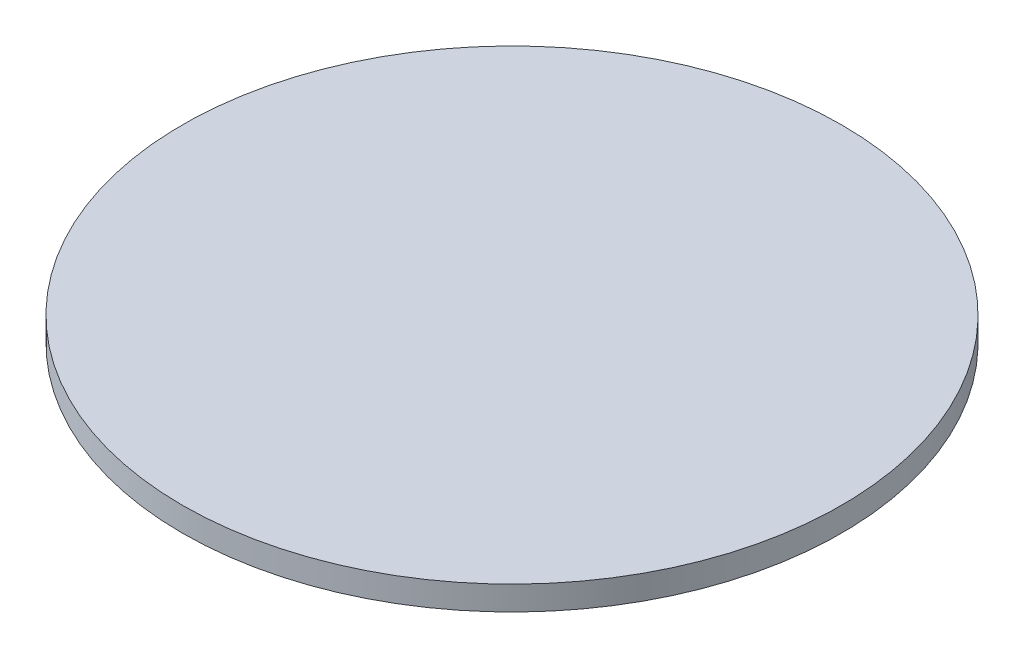
SolidWorks part; units mm, degrees
ref_plane "Front Plane" through (0, 0, 0) normal (0, 0, 1) x (1, 0, 0)
ref_plane "Top Plane" through (0, 0, 0) normal (0, 1, 0) x (1, 0, 0)
ref_plane "Right Plane" through (0, 0, 0) normal (1, 0, 0) x (0, 0, -1)
sketch "Sketch1" plane through (0, 0, 0) normal (0, 1, 0) x (1, 0, 0)
  circle A0 centre (0, 0) radius 15
  dimension "D1" = 30
extrude "Boss-Extrude1" add sketch "Sketch1" along normal blind 1.1
